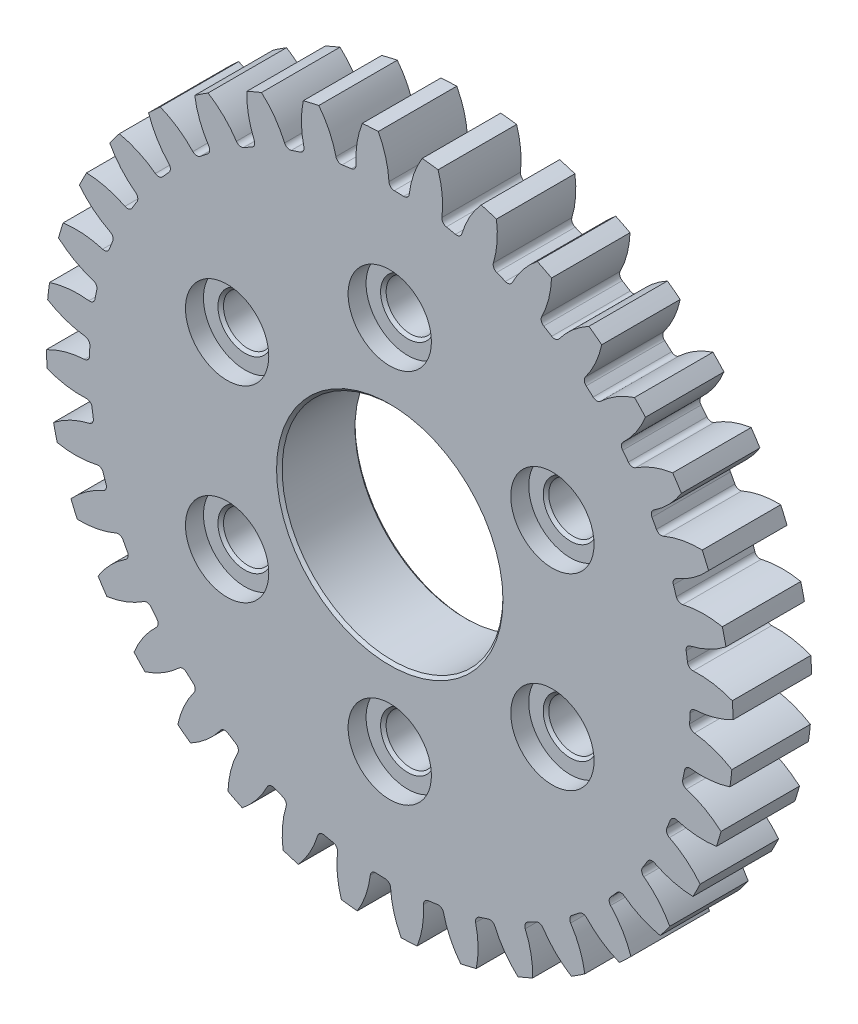
SolidWorks part; units mm, degrees
ref_plane "Front Plane" through (0, 0, 0) normal (0, 0, 1) x (1, 0, 0)
ref_plane "Top Plane" through (0, 0, 0) normal (0, 1, 0) x (1, 0, 0)
ref_plane "Right Plane" through (0, 0, 0) normal (1, 0, 0) x (0, 0, -1)
sketch "Sketch1" plane through (0, 0, 0) normal (0, 0, 1) x (1, 0, 0)
  circle A0 centre (0, 0) radius 23.4
  circle A1 centre (0, 0) radius 24.7
  circle A2 centre (0, 0) radius 21.58
  dimension "D1" = 46.8
  dimension "D2" = 49.4
  dimension "D3" = 3.12
extrude "Boss-Extrude1" add sketch "Sketch1" along normal mid plane 5.642 contours A2 | A0 A2 | A1 A0
sketch "Sketch3" plane through (0, 0, 2.821) normal (0, 0, 1) x (1, 0, 0)
  line L0 (0, 0) -> (0, 24.7) construction
  line L1 (-1.0207, 23.3777) -> (1.0207, 23.3777) construction
  line L2 (0, 0) -> (-0.7079, 21.5684) construction
  line L3 (0, 20.5885) -> (-1.8365, 25.6343) construction
  line L4 (0, 0) -> (2.1527, 24.606) construction
  line L5 (1.0207, 23.3777) -> (3.0543, 23.1998) construction
  circle A0 centre (0, 0) radius 24.7 construction
  arc A1 (-2.2399, 25.6022) -> (-0.7079, 21.5684) centre (-7.3591, 21.3501) cw
  arc A2 (2.2399, 25.6022) -> (0.7079, 21.5684) centre (7.3591, 21.3501) ccw
  circle A3 centre (0, 0) radius 21.58 construction
  arc A4 (0.7079, 21.5684) -> (-0.7079, 21.5684) centre (0, 0) ccw
  circle A6 centre (0, 0) radius 23.4 construction
  circle A7 centre (0, 0) radius 25.7
  arc A8 (2.2399, 25.6022) -> (-2.2399, 25.6022) centre (0, 0) ccw
  circle A9 centre (0, 0) radius 24.7 construction
  point P20 (2.0375, 23.2888)
  dimension "D2" = 20
  dimension "D3" = 5
sketch "Sketch4" plane through (0, 0, 0) normal (0, 1, 0) x (1, 0, 0)
  line L0 (0.7559, -2.821) -> (-0.7559, 2.821)
  line L1 (-24.7, -2.821) -> (24.7, -2.821) construction
  line L2 (24.7, 2.821) -> (-24.7, 2.821) construction
  line L3 (0, -3.2131) -> (0, 3.2131) construction
  dimension "D1" = 15
curve "Curve1"
sketch "Sketch5" plane through (0, 0, 2.821) normal (0, 0, 1) x (0.9995, -0.0306, 0)
  line L0 (0, 0) -> (0, 24.7) construction
  line L1 (-1.0207, 23.3777) -> (1.0207, 23.3777) construction
  line L2 (0, 0) -> (-0.7079, 21.5684) construction
  line L3 (0, 20.5885) -> (-1.8365, 25.6343) construction
  line L4 (0, 0) -> (2.1527, 24.606) construction
  line L5 (1.0207, 23.3777) -> (3.0543, 23.1998) construction
  arc A1 (-2.2399, 25.6022) -> (-0.7079, 21.5684) centre (-7.3591, 21.3501) cw
  arc A2 (2.2399, 25.6022) -> (0.7079, 21.5684) centre (7.3591, 21.3501) ccw
  arc A4 (0.7079, 21.5684) -> (-0.7079, 21.5684) centre (0, 0) ccw
  arc A8 (2.2399, 25.6022) -> (-2.2399, 25.6022) centre (0, 0) ccw
  point P20 (2.0375, 23.2888)
sketch "Sketch7" [suppressed] plane through (1.6622, 0.2826, -4.7625) normal (0, 0, 1) x (0.9724, 0.2332, 0)
  line L0 (0, 0) -> (0, 12.6) construction
  line L1 (-1.4097, 10.7076) -> (1.4097, 10.7076) construction
  line L2 (0, 0) -> (-0.707, 8.2498) construction
  line L3 (0, 6.9803) -> (-2.3358, 13.3979) construction
  line L4 (0, 0) -> (3.2611, 12.1707) construction
  line L5 (1.4097, 10.7076) -> (4.133, 9.9779) construction
  arc A1 (-3.5199, 13.1366) -> (-0.707, 8.2498) centre (-7.3467, 7.6808) cw
  arc A2 (3.5199, 13.1366) -> (0.707, 8.2498) centre (7.3467, 7.6808) ccw
  arc A4 (0.707, 8.2498) -> (-0.707, 8.2498) centre (0, 0) ccw
  arc A8 (3.5199, 13.1366) -> (-3.5199, 13.1366) centre (0, 0) ccw
  point P20 (2.7713, 10.3428)
loft "Cut-Loft1" [suppressed] cut profiles "Sketch7", "Sketch3"
fillet "Fillet2" [suppressed] radius 0.39
pattern_circular "CirPattern2" [suppressed] count 36 over 360
sketch "Sketch8" plane through (0, 0, 2.821) normal (0, 0, 1) x (1, 0, 0)
  line L0 (0, 24.7) -> (0, -24.7) construction
  line L1 (0, 0) -> (7.9375, 0) construction
  circle A0 centre (0, 0) radius 7.9375
  circle A1 centre (0, 0) radius 24.7 construction
  circle A2 centre (0, 13.5) radius 1.7526
  circle A3 centre (11.6913, 6.75) radius 1.7526
  circle A4 centre (11.6913, -6.75) radius 1.7526
  circle A5 centre (0, -13.5) radius 1.7526
  circle A6 centre (-11.6913, -6.75) radius 1.7526
  circle A7 centre (-11.6913, 6.75) radius 1.7526
  spline S0 degree 3 poles (-0.7559, 24.6884) (-0.252, 24.7039) (0.252, 24.7039) (0.7559, 24.6884) knots 0 0 0 0 1 1 1 1 weights 1 0.999688 0.999688 1 construction
  point P26 (0, 0)
  dimension "D1" = 15.875
  dimension "D2" = 13.5
  dimension "D3" = 3.5052
  dimension "D4" = 6
extrude "Cut-Extrude1" cut sketch "Sketch8" against normal through all
extrude "Cut-Extrude2" cut sketch "Sketch5" against normal through all
fillet "Fillet3" radius 0.39 2 edges at (-0.0475, 21.5799, 0) (1.3676, 21.5366, 0)
pattern_circular "CirPattern3" count 36 over 360 about axis through (0, 0, 0) along (0, 0, 1) of "Cut-Extrude2", "Fillet3"
sketch "Sketch9" plane through (0, 0, 2.821) normal (0, 0, 1) x (1, 0, 0)
  line L0 (0, 0) -> (0, 11.1125) construction
  line L1 (0, 0) -> (9.6237, 5.5563) construction
  circle A0 centre (0, 0) radius 11.1125 construction
  circle A1 centre (0, 0) radius 19.05 construction
  circle A2 centre (0, 13.5) radius 2.994
  circle A3 centre (11.6913, 6.75) radius 2.994
  circle A4 centre (11.6913, -6.75) radius 2.994
  circle A5 centre (0, -13.5) radius 2.994
  circle A6 centre (-11.6913, -6.75) radius 2.994
  circle A7 centre (-11.6913, 6.75) radius 2.994
  point P23 (0, 0)
  dimension "D1" = 22.225
  dimension "D3" = 5.988
  dimension "D2" = 7.9375
  dimension "D4" = 6
extrude "Cut-Extrude3" cut sketch "Sketch9" against normal blind 1.292
chamfer "Chamfer1" distance 0.2 angle 45 8 edges at (7.9375, 0, 2.821) (7.9375, 0, -2.821) (-9.9387, -6.75, 1.529) (1.7526, -13.5, 1.529) (13.4439, -6.75, 1.529) (13.4439, 6.75, 1.529) (1.7526, 13.5, 1.529) (-9.9387, 6.75, 1.529)
sketch "Sketch10" plane through (0, 0, 2.821) normal (0, 0, 1) x (1, 0, 0)
  line L0 (0, 0) -> (2.9047, 24.5286) construction
  line L1 (0, 0) -> (7.12, 23.6516) construction
  line L2 (2.9047, 24.5286) -> (14.5404, 23.1507) construction
  line L3 (2.9047, 24.5286) -> (8.0644, 24.5286) construction
  line L4 (-0.8247, 24.6862) -> (2.3169, 24.8644) construction
  line L5 (-0.8247, 24.6862) -> (1.7618, 24.6862) construction
  line L6 (-2.3498, 23.2405) -> (-0.2932, 23.3572) construction
  arc A0 (6.2206, 20.664) -> (2.5378, 21.4303) centre (0, 0) ccw construction
  arc A1 (3.4746, 24.4544) -> (2.3333, 24.5895) centre (0, 0) ccw construction
  arc A2 (7.6683, 23.4795) -> (6.5678, 23.8108) centre (0, 0) ccw construction
  arc A3 (2.9047, 24.5286) -> (7.12, 23.6516) centre (0, 0) cw construction
  arc A5 (-1.972, 24.6211) -> (-2.4235, 21.8111) centre (4.2207, 22.1849) ccw construction
  arc A6 (-0.0583, 21.9452) -> (-0.8247, 24.6862) centre (-6.7022, 21.5653) ccw construction
  dimension "D1" = 3.246
equation "\"Module\"= 1.3mm"
equation "\"Number of Teeth\"= 36"
equation "\"D1@Sketch1\"=\"Module\" * \"Number of Teeth\""
equation "\"D2@Sketch1\"=(\"Number of Teeth\" + 2) * \"Module\""
equation "\"D3@Sketch1\"=\"Module\" * if(  \"Module\" => 1.25, 2.25, 2.4)"
equation "\"D3@Sketch3\"=180 / \"Number of Teeth\""
equation "\"D1@Fillet2\"= \"Module\" * 0.3"
equation "\"D1@CirPattern2\"= \"Number of Teeth\""
equation "\"D1@Fillet3\"=\"Module\"*.3"
equation "\"D1@CirPattern3\"=\"Number of Teeth\""
